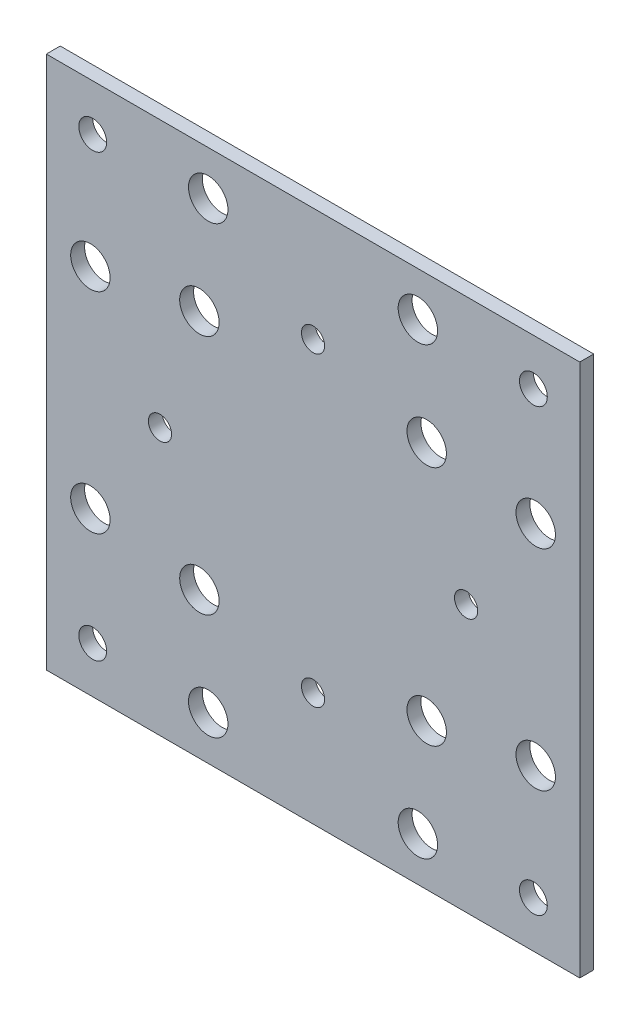
SolidWorks part; units mm, degrees
material "玻纤板"
ref_plane "前视基准面" through (0, 0, 0) normal (0, 0, 1) x (1, 0, 0)
ref_plane "上视基准面" through (0, 0, 0) normal (0, 1, 0) x (1, 0, 0)
ref_plane "右视基准面" through (0, 0, 0) normal (1, 0, 0) x (0, 0, -1)
other "Configuration Table"
sketch "草图1" plane through (0, 0, 0) normal (0, 0, 1) x (1, 0, 0)
  line L1 (-57.5, -57.5) -> (57.5, -57.5)
  line L2 (-57.5, -57.5) -> (-57.5, 57.5)
  line L3 (-57.5, 57.5) -> (57.5, 57.5)
  line L4 (57.5, -57.5) -> (57.5, 57.5)
  line L5 (-57.5, -57.5) -> (57.5, 57.5) construction
  line L6 (-57.5, 57.5) -> (57.5, -57.5) construction
  point P0 (0, 0)
  dimension "D1" = 115
  dimension "D2" = 115
extrude "凸台-拉伸1" add sketch "草图1" along normal blind 3
sketch "草图3" plane through (0, 0, 3) normal (0, 0, 1) x (1, 0, 0)
  line L1 (-47.5, -47.5) -> (47.5, -47.5) construction
  line L2 (-47.5, -47.5) -> (-47.5, 47.5) construction
  line L3 (-47.5, 47.5) -> (47.5, 47.5) construction
  line L4 (47.5, -47.5) -> (47.5, 47.5) construction
  line L5 (-47.5, -47.5) -> (47.5, 47.5) construction
  line L6 (-47.5, 47.5) -> (47.5, -47.5) construction
  circle A0 centre (-47.5, 47.5) radius 3
  circle A1 centre (47.5, 47.5) radius 3
  circle A2 centre (47.5, -47.5) radius 3
  circle A3 centre (-47.5, -47.5) radius 3
  point P0 (0, 0)
  dimension "D3" = 6
  dimension "D1" = 95
  dimension "D2" = 95
extrude "切除-拉伸2" cut sketch "草图3" against normal through all
sketch "草图4" plane through (0, 0, 3) normal (0, 0, 1) x (1, 0, 0)
  line L0 (-57.5, -57.5) -> (57.5, -57.5) construction
  line L1 (0, 0) -> (0, -57.5) construction
  line L2 (-57.5, 0) -> (57.5, 0) construction
  line L3 (-57.5, 57.5) -> (-57.5, -57.5) construction
  line L4 (57.5, -57.5) -> (57.5, 57.5) construction
  circle A0 centre (-22.6, -48) radius 4.25
  circle A1 centre (22.6, -48) radius 4.25
  circle A2 centre (-48, -22.6) radius 4.25
  circle A3 centre (-48, 22.6) radius 4.25
  circle A4 centre (48, -22.6) radius 4.25
  circle A5 centre (48, 22.6) radius 4.25
  circle A6 centre (22.6, 48) radius 4.25
  circle A7 centre (-22.6, 48) radius 4.25
  circle A8 centre (-33, 0) radius 2.5
  circle A9 centre (0, -33) radius 2.5
  circle A10 centre (0, 33) radius 2.5
  circle A11 centre (33, 0) radius 2.5
  dimension "D2" = 45.2
  dimension "D3" = 8.5
  dimension "D5" = 8.5
  dimension "D6" = 45.2
  dimension "D7" = 66
  dimension "D8" = 66
  dimension "D9" = 5
  dimension "D10" = 5
  dimension "D1" = 9.5
  dimension "D4" = 9.5
extrude "切除-拉伸3" cut sketch "草图4" against normal up to surface (3 mm away) up to face at (-44.5, -47.5, 0)
sketch "草图5" plane through (0, 0, 3) normal (0, 0, 1) x (1, 0, 0)
  line L0 (-57.5, 57.5) -> (-57.5, -57.5) construction
  line L1 (57.5, 57.5) -> (-57.5, 57.5) construction
  line L2 (0, 0) -> (57.5, 0) construction
  line L3 (57.5, -57.5) -> (57.5, 57.5) construction
  line L4 (0, 0) -> (0, 57.5) construction
  circle A0 centre (-24.5, 26) radius 4.25
  circle A1 centre (-24.5, -26) radius 4.25
  circle A2 centre (24.5, 26) radius 4.25
  circle A3 centre (24.5, -26) radius 4.25
  dimension "D2" = 31.5
  dimension "D3" = 8.5
  dimension "D1" = 33
extrude "切除-拉伸4" cut sketch "草图5" against normal up to surface (3 mm away) up to face at (-35.5, 0, 0)
